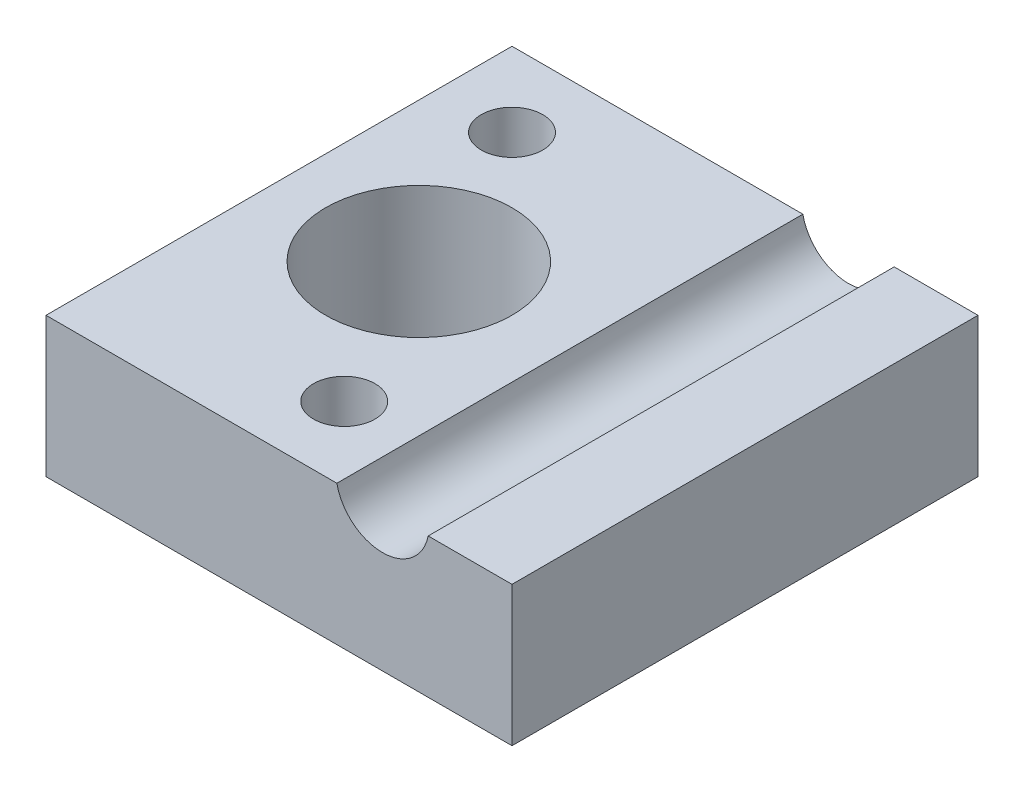
SolidWorks part; units mm, degrees
ref_plane "Plan de face" through (0, 0, 0) normal (0, 0, 1) x (1, 0, 0)
ref_plane "Plan de dessus" through (0, 0, 0) normal (0, 1, 0) x (1, 0, 0)
ref_plane "Plan de droite" through (0, 0, 0) normal (1, 0, 0) x (0, 0, -1)
sketch "Esquisse1" plane through (0, 0, 0) normal (0, 0, 1) x (1, 0, 0)
  line L0 (-36.1083, -1) -> (-36.1083, -16)
  line L1 (-36.1083, -16) -> (13.8917, -16)
  line L2 (13.8917, -16) -> (13.8917, -1)
  line L3 (13.8917, -1) -> (4.899, -1)
  line L4 (-4.899, -1) -> (-36.1083, -1)
  arc A0 (4.899, -1) -> (-4.899, -1) centre (0, 0) cw
  circle A1 centre (0, 0) radius 5 construction
  dimension "D1" = 50
  dimension "D2" = 15
  dimension "D3" = 1
extrude "Boss.-Extru.1" add sketch "Esquisse1" along normal blind 50
hole_wizard "Chambrage pour vis à tête hexagonale M62" positions "Esquisse4" profile "Esquisse3" counterbore size "M6" standard "Iso" end condition through all
sketch "Esquisse4" plane through (0, -16, 0) normal (0, -1, 0) x (-1, 0, 0)
  line L0 (36.1083, -50) -> (-13.8917, -50) construction
  line L3 (36.1083, -50) -> (36.1083, 0) construction
  line L4 (36.1083, 0) -> (-13.8917, 0) construction
  point P0 (12.1083, -42)
  point P2 (28.1083, -8)
  point P12 (5, -54.575)
  point P19 (5, -51.5799)
  dimension "D1" = 8
  dimension "D2" = 8
  dimension "D3" = 8
  dimension "D4" = 16
sketch "Esquisse3" plane through (-12.1083, -16, 42) normal (1, 0, 0) x (0, 0, -1)
  line L0 (0, 0) -> (0, 15)
  line L1 (0, 15) -> (3.3, 15)
  line L3 (3.3, 15) -> (3.3, 6.4)
  line L4 (3.3, 6.4) -> (5.5, 6.4)
  line L5 (5.5, 6.4) -> (5.5, 0)
  line L7 (5.5, 0) -> (0, 0)
  line L11 (0, -6.35) -> (0, 107.95) construction
  dimension "Diamètre du perçage jusqu'au prochain" = 6.6
  dimension "Profondeur du perçage jusqu'au prochain" = 15
  dimension "Diamètre du chambrage" = 11
  dimension "Profondeur du chambrage" = 6.4
sketch "Esquisse5" plane through (0, -16, 0) normal (0, -1, 0) x (-1, 0, 0)
  line L0 (36.1083, -50) -> (36.1083, 0) construction
  line L1 (4.899, -50) -> (36.1083, -50) construction
  circle A0 centre (21.1083, -25) radius 10
  dimension "D3" = 20
  dimension "D1" = 15
  dimension "D2" = 25
extrude "Enlèv. mat.-Extru.1" cut sketch "Esquisse5" against normal through all
